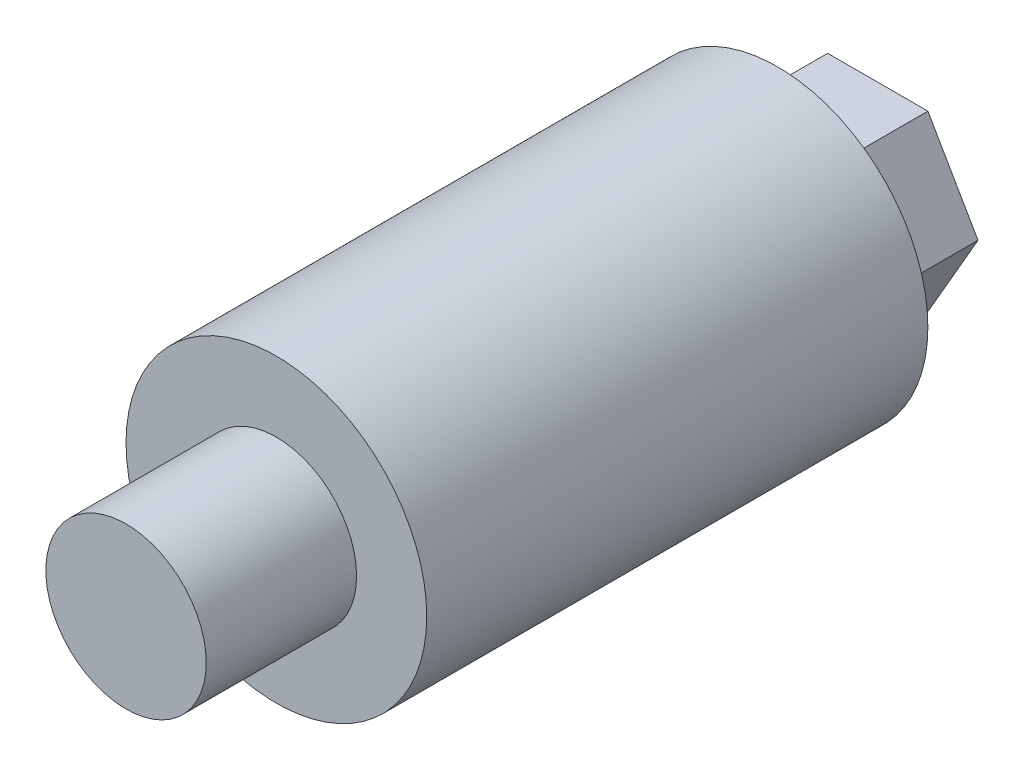
SolidWorks part; units mm, degrees
ref_plane "Piano frontale" through (0, 0, 0) normal (0, 0, 1) x (1, 0, 0)
ref_plane "Piano superiore" through (0, 0, 0) normal (0, 1, 0) x (1, 0, 0)
ref_plane "Piano destro" through (0, 0, 0) normal (1, 0, 0) x (0, 0, -1)
sketch "Schizzo1" plane through (0, 0, 0) normal (0, 0, 1) x (1, 0, 0)
  circle A0 centre (0, 0) radius 15
extrude "Estrusione-Estrusione1" add sketch "Schizzo1" along normal blind 50
sketch "Schizzo2" plane through (0, 0, 50) normal (0, 0, 1) x (1, 0, 0)
  circle A0 centre (0, 0) radius 8
extrude "Estrusione-Estrusione2" add sketch "Schizzo2" along normal blind 15
sketch "Schizzo3" plane through (0, 0, 0) normal (0, 0, -1) x (-1, 0, 0)
  line L1 (10, 0) -> (5, 8.6603)
  line L2 (5, 8.6603) -> (-5, 8.6603)
  line L3 (-5, 8.6603) -> (-10, 0)
  line L4 (-10, 0) -> (-5, -8.6603)
  line L5 (-5, -8.6603) -> (5, -8.6603)
  line L6 (5, -8.6603) -> (10, 0)
  circle A0 centre (0, 0) radius 8.6603 construction
  dimension "D1" = 10
extrude "Estrusione-Estrusione3" add sketch "Schizzo3" along normal blind 10
